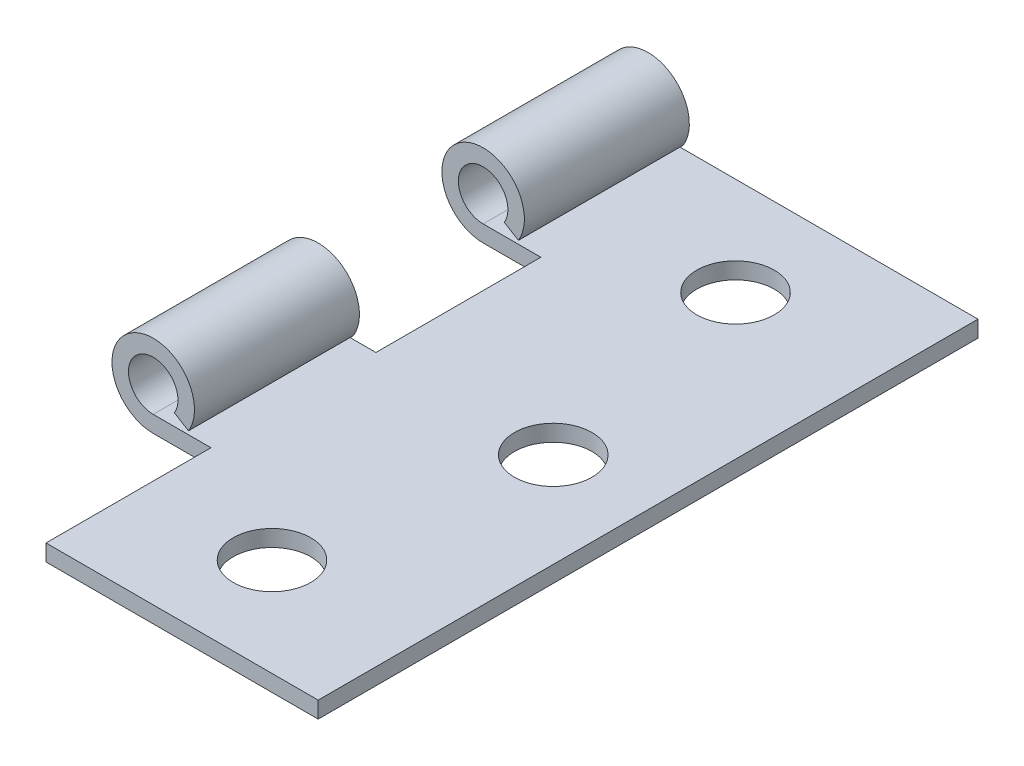
SolidWorks part; units mm, degrees
ref_plane "Front Plane" through (0, 0, 0) normal (0, 0, 1) x (1, 0, 0)
ref_plane "Top Plane" through (0, 0, 0) normal (0, 1, 0) x (1, 0, 0)
ref_plane "Right Plane" through (0, 0, 0) normal (1, 0, 0) x (0, 0, -1)
sketch "Sketch1" plane through (0, 0, 0) normal (0, 0, 1) x (1, 0, 0)
  line L0 (20, -1.5) -> (0, -1.5)
  arc A0 (0, -1.5) -> (1.2833, -0.7766) centre (0, 0) cw
  dimension "D1" = 1.5
  dimension "D2" = 20
extrude "Extrude-Thin2" add sketch "Sketch1" along normal blind 40 thin thin type one direction reverse wall 1
sketch "Sketch2" plane through (0, 0, 0) normal (0, 1, 0) x (1, 0, 0)
  line L0 (-2.5, 0) -> (-2.5, -40) construction
  line L1 (-2.5, -10) -> (3.5, -10)
  line L2 (-2.5, -10) -> (-2.5, -20)
  line L3 (-2.5, -20) -> (3.5, -20)
  line L4 (3.5, -10) -> (3.5, -20)
  line L5 (20, -40) -> (0, -40) construction
  line L6 (-2.5, -30) -> (3.5, -30)
  line L7 (-2.5, -30) -> (-2.5, -40)
  line L8 (-2.5, -40) -> (3.5, -40)
  line L9 (3.5, -30) -> (3.5, -40)
  dimension "D1" = 6
  dimension "D2" = 10
  dimension "D3" = 10
  dimension "D4" = 10
extrude "Cut-Extrude1" cut sketch "Sketch2" against normal through all both and the other way through all
sketch "Sketch3" plane through (0, 0, 0) normal (0, 1, 0) x (1, 0, 0)
  line L0 (11.25, -34.05) -> (11.25, -5.95) construction
  line L1 (11.25, -20) -> (20, -20) construction
  line L2 (20, -40) -> (20, 0) construction
  line L3 (20, -40) -> (3.5, -40) construction
  circle A0 centre (14.25, -20) radius 2.35
  circle A1 centre (11.25, -34.05) radius 2.35
  circle A2 centre (11.25, -5.95) radius 2.35
  point P6 (14.25, -20)
  dimension "D1" = 4.7
  dimension "D2" = 5.75
  dimension "D3" = 5.95
  dimension "D4" = 8.75
extrude "Cut-Extrude2" cut sketch "Sketch3" against normal blind 10
